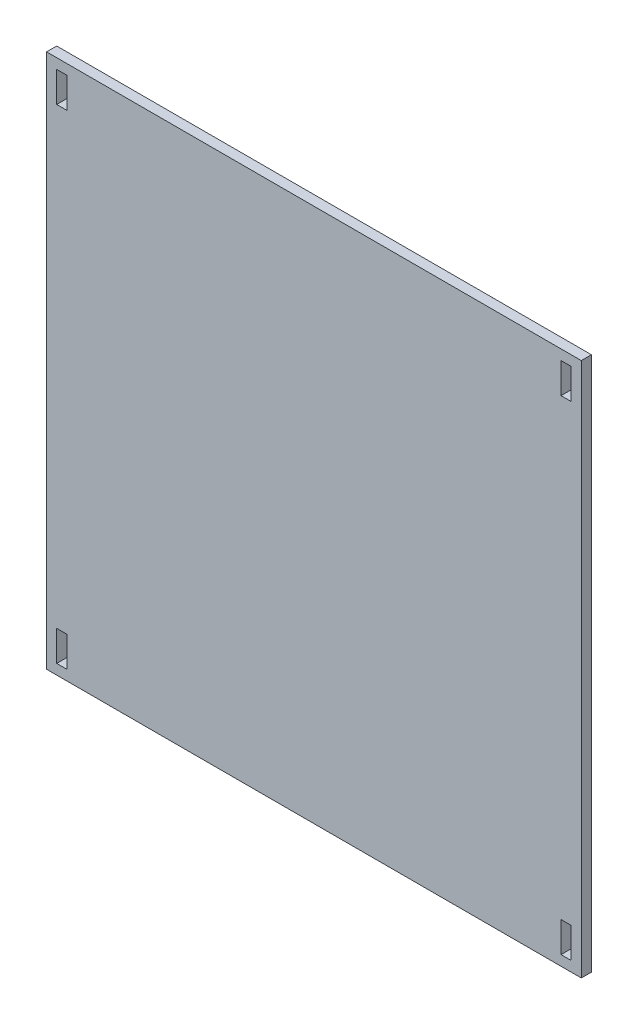
SolidWorks part; units mm, degrees
material "PVC Rigid"
ref_plane "Front Plane" through (0, 0, 0) normal (0, 0, 1) x (1, 0, 0)
ref_plane "Top Plane" through (0, 0, 0) normal (0, 1, 0) x (1, 0, 0)
ref_plane "Right Plane" through (0, 0, 0) normal (1, 0, 0) x (0, 0, -1)
sketch "Sketch1" plane through (0, 0, 0) normal (0, 0, 1) x (1, 0, 0)
  line L1 (0, 0) -> (-528, 0)
  line L2 (0, 0) -> (0, 528)
  line L3 (0, 528) -> (-528, 528)
  line L4 (-528, 0) -> (-528, 528)
  dimension "D1" = 528
  dimension "D2" = 528
extrude "Boss-Extrude1" add sketch "Sketch1" along normal blind 10
sketch "Sketch2" plane through (0, 0, 0) normal (0, 0, -1) x (-1, 0, 0)
  line L0 (528, 528) -> (528, 0) construction
  line L1 (518, 518) -> (508, 518)
  line L2 (518, 518) -> (518, 488)
  line L3 (518, 488) -> (508, 488)
  line L4 (508, 518) -> (508, 488)
  line L5 (518, 40) -> (508, 40)
  line L6 (518, 40) -> (518, 10)
  line L7 (518, 10) -> (508, 10)
  line L8 (508, 40) -> (508, 10)
  line L9 (10, 10) -> (20, 10)
  line L10 (10, 10) -> (10, 40)
  line L11 (10, 40) -> (20, 40)
  line L12 (20, 10) -> (20, 40)
  line L13 (10, 518) -> (20, 518)
  line L14 (10, 518) -> (10, 488)
  line L15 (10, 488) -> (20, 488)
  line L16 (20, 518) -> (20, 488)
  line L17 (0, 528) -> (528, 528) construction
  line L18 (528, 0) -> (0, 0) construction
  line L19 (0, 0) -> (0, 528) construction
  point P20 (513, 518)
  dimension "D1" = 10
  dimension "D2" = 10
  dimension "D3" = 10
  dimension "D4" = 30
  dimension "D5" = 10
  dimension "D6" = 10
  dimension "D7" = 10
  dimension "D8" = 30
  dimension "D9" = 10
  dimension "D10" = 10
  dimension "D11" = 10
  dimension "D12" = 30
  dimension "D13" = 10
  dimension "D14" = 10
  dimension "D15" = 10
  dimension "D16" = 30
extrude "Cut-Extrude1" cut sketch "Sketch2" against normal blind 10
